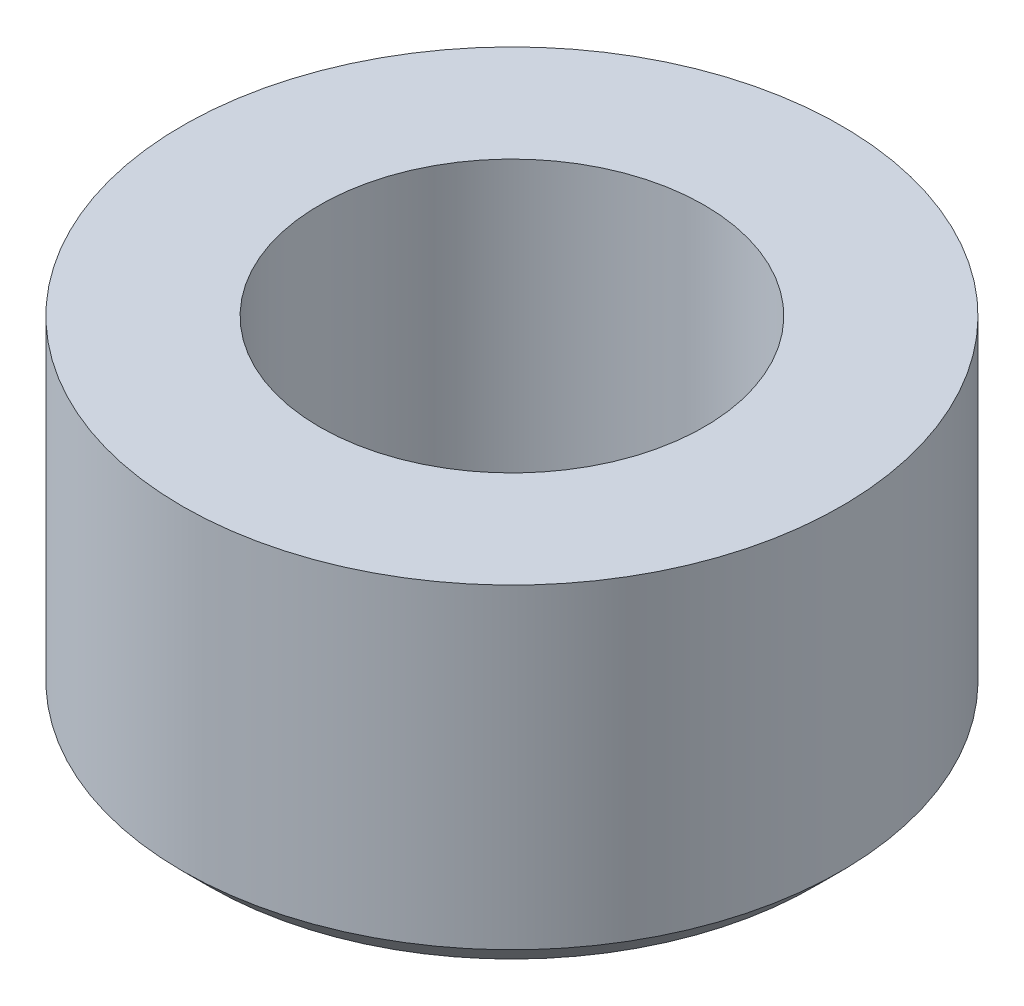
SolidWorks part; units mm, degrees
ref_plane "Front Plane" through (0, 0, 0) normal (0, 0, 1) x (1, 0, 0)
ref_plane "Top Plane" through (0, 0, 0) normal (0, 1, 0) x (1, 0, 0)
ref_plane "Right Plane" through (0, 0, 0) normal (1, 0, 0) x (0, 0, -1)
sketch "Sketch1" plane through (0, 0, 0) normal (0, 1, 0) x (1, 0, 0)
  circle A0 centre (0, 0) radius 3.556
  circle A1 centre (0, 0) radius 6.096
  dimension "D2" = 12.192
  dimension "D1" = 7.112
extrude "Boss-Extrude1" add sketch "Sketch1" along normal blind 6.35
chamfer "Chamfer1" distance 0.508 angle 45 1 edges at (0, 0, 6.096)
